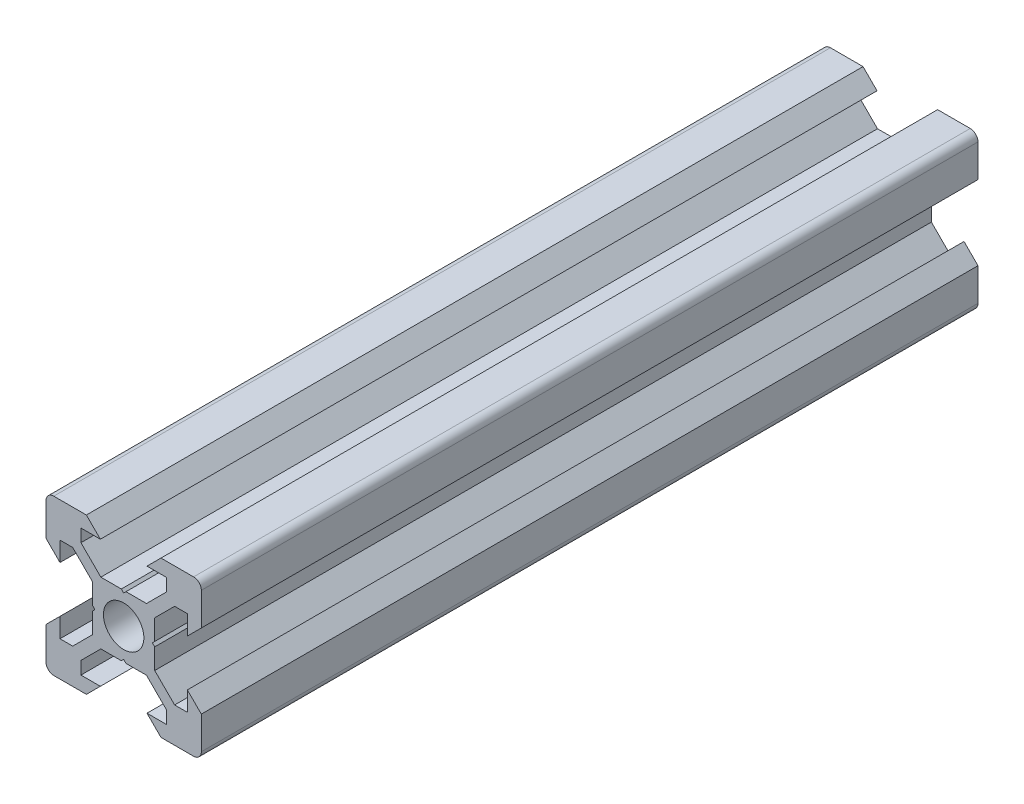
SolidWorks part; units mm, degrees
material "1060-H12 Rod (SS)"
ref_plane "Front Plane" through (0, 0, 0) normal (0, 0, 1) x (1, 0, 0)
ref_plane "Top Plane" through (0, 0, 0) normal (0, 1, 0) x (1, 0, 0)
ref_plane "Right Plane" through (0, 0, 0) normal (1, 0, 0) x (0, 0, -1)
sketch "Sketch1" plane through (0, 0, 0) normal (0, 0, 1) x (1, 0, 0)
  line B0 (10.3368, -8.1134) -> (10.3368, -3.9134)
  line B1 (10.3368, -3.9134) -> (8.5368, -2.1134)
  line B2 (8.5368, -2.1134) -> (8.5368, -4.6134)
  line B3 (8.5368, -4.6134) -> (6.8974, -4.6134)
  line B4 (6.8974, -4.6134) -> (4.3368, -2.0527)
  line B5 (4.3368, -2.0527) -> (4.3368, 0.5866)
  line B6 (4.3368, 0.5866) -> (4.0368, 0.8866)
  line B7 (4.0368, 0.8866) -> (4.3368, 1.1866)
  line B8 (4.3368, 1.1866) -> (4.3368, 3.826)
  line B9 (4.3368, 3.826) -> (6.8974, 6.3866)
  line B10 (6.8974, 6.3866) -> (8.5368, 6.3866)
  line B11 (8.5368, 6.3866) -> (8.5368, 3.8866)
  line B12 (8.5368, 3.8866) -> (10.3368, 5.6866)
  line B13 (10.3368, 5.6866) -> (10.3368, 9.8866)
  line B14 (9.3368, 10.8866) -> (5.1368, 10.8866)
  line B15 (5.1368, 10.8866) -> (3.3368, 9.0866)
  line B16 (3.3368, 9.0866) -> (5.8368, 9.0866)
  line B17 (5.8368, 9.0866) -> (5.8368, 7.4473)
  line B18 (5.8368, 7.4473) -> (3.2761, 4.8866)
  line B19 (3.2761, 4.8866) -> (0.6368, 4.8866)
  line B20 (0.6368, 4.8866) -> (0.3368, 4.5866)
  line B21 (0.3368, 4.5866) -> (0.0368, 4.8866)
  line B22 (0.0368, 4.8866) -> (-2.6026, 4.8866)
  line B23 (-2.6026, 4.8866) -> (-5.1632, 7.4473)
  line B24 (-5.1632, 7.4473) -> (-5.1632, 9.0866)
  line B25 (-5.1632, 9.0866) -> (-2.6632, 9.0866)
  line B26 (-2.6632, 9.0866) -> (-4.4632, 10.8866)
  line B27 (-4.4632, 10.8866) -> (-8.6632, 10.8866)
  line B28 (-9.6632, 9.8866) -> (-9.6632, 5.6866)
  line B29 (-9.6632, 5.6866) -> (-7.8632, 3.8866)
  line B30 (-7.8632, 3.8866) -> (-7.8632, 6.3866)
  line B31 (-7.8632, 6.3866) -> (-6.2239, 6.3866)
  line B32 (-6.2239, 6.3866) -> (-3.6632, 3.826)
  line B33 (-3.6632, 3.826) -> (-3.6632, 1.1866)
  line B34 (-3.6632, 1.1866) -> (-3.3632, 0.8866)
  line B35 (-3.3632, 0.8866) -> (-3.6632, 0.5866)
  line B36 (-3.6632, 0.5866) -> (-3.6632, -2.0527)
  line B37 (-3.6632, -2.0527) -> (-6.2239, -4.6134)
  line B38 (-6.2239, -4.6134) -> (-7.8632, -4.6134)
  line B39 (-7.8632, -4.6134) -> (-7.8632, -2.1134)
  line B40 (-7.8632, -2.1134) -> (-9.6632, -3.9134)
  line B41 (-9.6632, -3.9134) -> (-9.6632, -8.1134)
  line B42 (-8.6632, -9.1134) -> (-4.4632, -9.1134)
  line B43 (-4.4632, -9.1134) -> (-2.6632, -7.3134)
  line B44 (-2.6632, -7.3134) -> (-5.1632, -7.3134)
  line B45 (-5.1632, -7.3134) -> (-5.1632, -5.674)
  line B46 (-5.1632, -5.674) -> (-2.6026, -3.1134)
  line B47 (-2.6026, -3.1134) -> (0.0368, -3.1134)
  line B48 (0.0368, -3.1134) -> (0.3368, -2.8134)
  line B49 (0.3368, -2.8134) -> (0.6368, -3.1134)
  line B50 (0.6368, -3.1134) -> (3.2761, -3.1134)
  line B51 (3.2761, -3.1134) -> (5.8368, -5.674)
  line B52 (5.8368, -5.674) -> (5.8368, -7.3134)
  line B53 (5.8368, -7.3134) -> (3.3368, -7.3134)
  line B54 (3.3368, -7.3134) -> (5.1368, -9.1134)
  line B55 (5.1368, -9.1134) -> (9.3368, -9.1134)
  arc B56 (9.3368, -9.1134) -> (10.3368, -8.1134) centre (9.3368, -8.1134) ccw
  arc B57 (10.3368, 9.8866) -> (9.3368, 10.8866) centre (9.3368, 9.8866) ccw
  arc B58 (-8.6632, 10.8866) -> (-9.6632, 9.8866) centre (-8.6632, 9.8866) ccw
  arc B59 (-9.6632, -8.1134) -> (-8.6632, -9.1134) centre (-8.6632, -8.1134) ccw
  circle B60 centre (0.3368, 0.8866) radius 2.6
sketch_block_instance "AL profile  block  -1"
sketch_block "AL profile  block  " parameters "D1"=3.2452
extrude "Boss-Extrude1" add sketch "Sketch1" along normal blind 100
